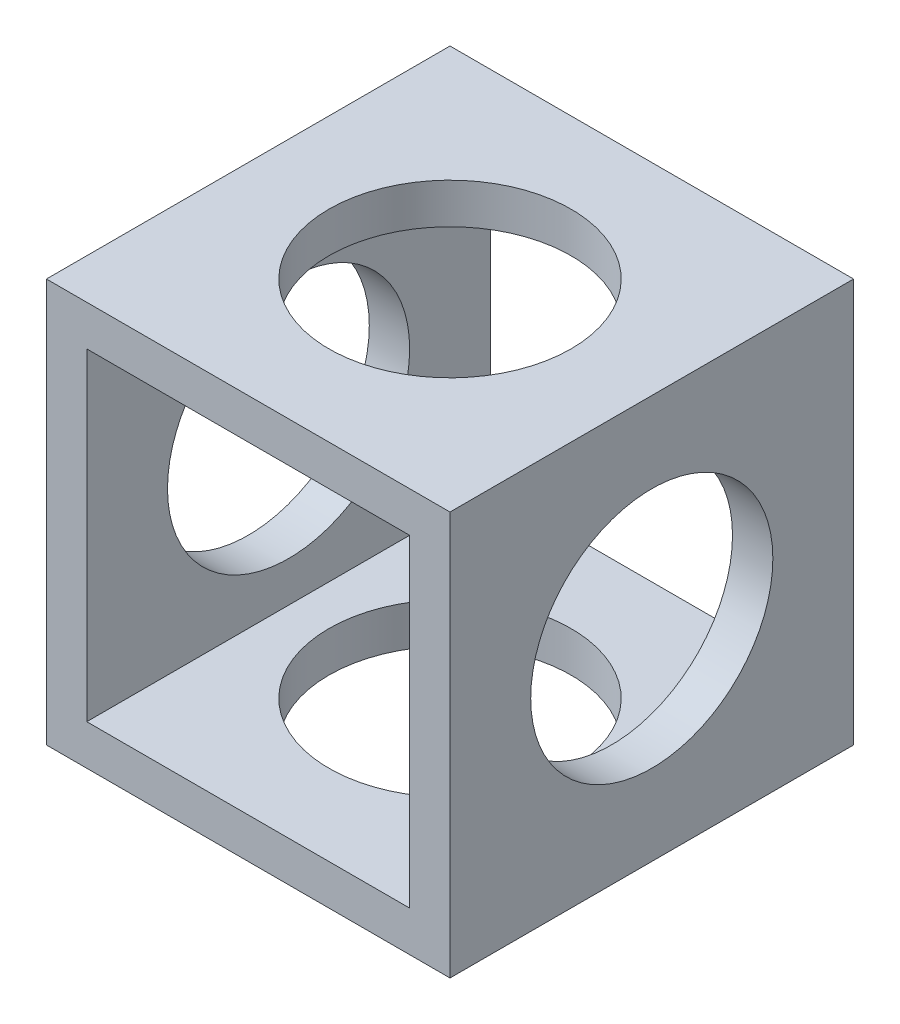
SolidWorks part; units mm, degrees
ref_plane "Alzado" through (0, 0, 0) normal (0, 0, 1) x (1, 0, 0)
ref_plane "Planta" through (0, 0, 0) normal (0, 1, 0) x (1, 0, 0)
ref_plane "Vista lateral" through (0, 0, 0) normal (1, 0, 0) x (0, 0, -1)
sketch "Croquis1" plane through (0, 0, 0) normal (0, 0, 1) x (1, 0, 0)
  line L1 (25, -25) -> (-25, -25)
  line L2 (25, -25) -> (25, 25)
  line L3 (25, 25) -> (-25, 25)
  line L4 (-25, -25) -> (-25, 25)
  line L5 (25, -25) -> (-25, 25) construction
  line L6 (25, 25) -> (-25, -25) construction
  line L7 (20, -20) -> (-20, -20)
  line L8 (20, -20) -> (20, 20)
  line L9 (20, 20) -> (-20, 20)
  line L10 (-20, -20) -> (-20, 20)
  line L11 (20, -20) -> (-20, 20) construction
  line L12 (20, 20) -> (-20, -20) construction
  point P0 (0, 0)
  point P6 (0, 0)
  dimension "D1" = 50
  dimension "D2" = 50
  dimension "D3" = 40
extrude "Saliente-Extruir1" add sketch "Croquis1" against normal blind 50
sketch "Croquis2" plane through (0, 25, 0) normal (0, 1, 0) x (1, 0, 0)
  line L0 (-25, 50) -> (25, 0) construction
  line L4 (-25, 0) -> (25, 0)
  line L5 (25, 0) -> (25, 50)
  line L6 (25, 50) -> (-25, 50)
  line L7 (-25, 50) -> (-25, 0)
  line L8 (-25, 0) -> (25, 0)
  line L9 (25, 0) -> (25, 50)
  line L10 (25, 50) -> (-25, 50)
  line L11 (-25, 50) -> (-25, 0)
  circle A0 centre (0, 25) radius 15
  dimension "D2" = 30
  dimension "D1" = 0
extrude "Cortar-Extruir1" cut sketch "Croquis2" against normal through all contours A0
sketch "Croquis3" plane through (25, 0, 0) normal (1, 0, 0) x (0, 0, -1)
  line L0 (25, 25) -> (25, -25) construction
  line L4 (0, 25) -> (0, -25)
  line L5 (0, -25) -> (50, -25)
  line L6 (50, -25) -> (50, 25)
  line L7 (50, 25) -> (0, 25)
  line L8 (0, 25) -> (0, -25)
  line L9 (0, -25) -> (50, -25)
  line L10 (50, -25) -> (50, 25)
  line L11 (50, 25) -> (0, 25)
  circle A0 centre (25, 0) radius 15
  dimension "D2" = 30
  dimension "D1" = 0
extrude "Cortar-Extruir2" cut sketch "Croquis3" against normal through all contours A0
